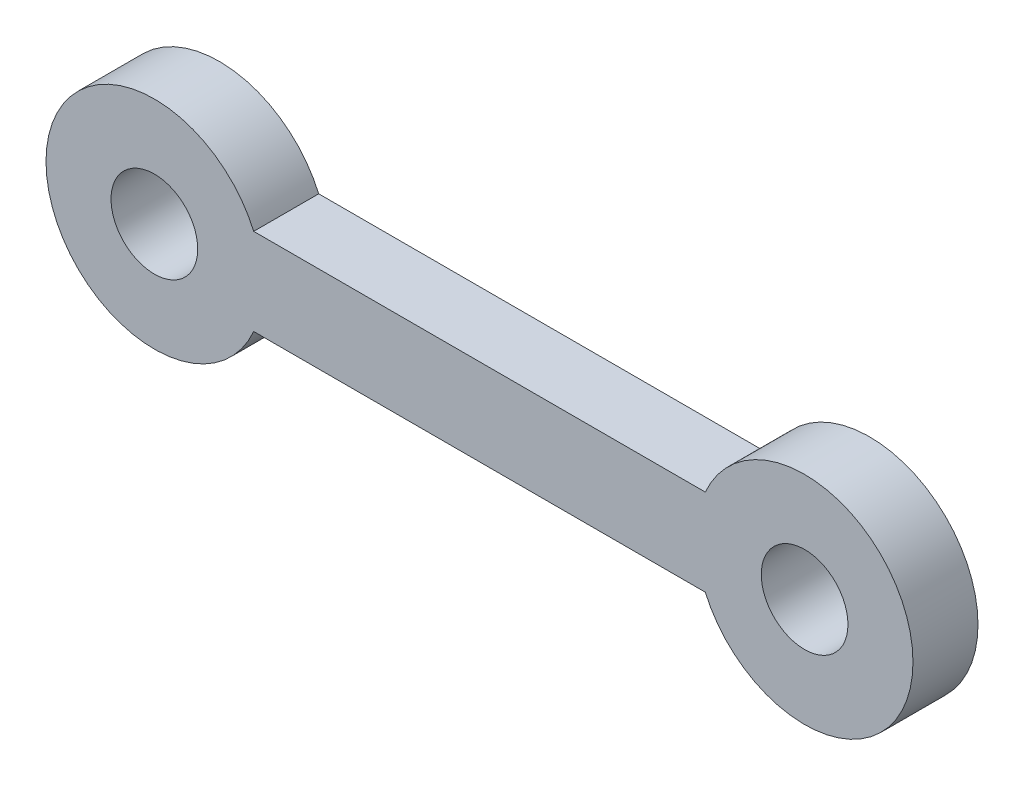
SolidWorks part; units mm, degrees
ref_plane "前视基准面" through (0, 0, 0) normal (0, 0, 1) x (1, 0, 0)
ref_plane "上视基准面" through (0, 0, 0) normal (0, 1, 0) x (1, 0, 0)
ref_plane "右视基准面" through (0, 0, 0) normal (1, 0, 0) x (0, 0, -1)
sketch "草图2" plane through (0, 0, 0) normal (0, 0, 1) x (1, 0, 0)
  line L0 (0, 0) -> (30, 0) construction
  line L1 (55, 0) -> (-55, 0) construction
  line L2 (4.5826, 2) -> (25.4174, 2)
  line L3 (4.5826, -2) -> (25.4174, -2)
  arc A2 (4.5826, 2) -> (4.5826, -2) centre (0, 0) ccw
  arc A3 (25.4174, -2) -> (25.4174, 2) centre (30, 0) ccw
  circle A4 centre (0, 0) radius 2
  circle A5 centre (30, 0) radius 2
  point P5 (15, 0)
extrude "凸台-拉伸1" add sketch "草图2" along normal mid plane 3
